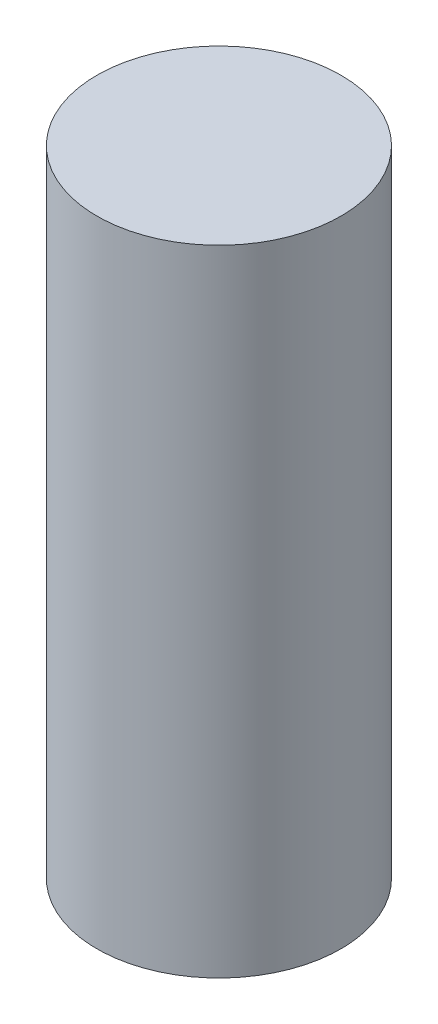
SolidWorks part; units mm, degrees
ref_plane "Front Plane" through (0, 0, 0) normal (0, 0, 1) x (1, 0, 0)
ref_plane "Top Plane" through (0, 0, 0) normal (0, 1, 0) x (1, 0, 0)
ref_plane "Right Plane" through (0, 0, 0) normal (1, 0, 0) x (0, 0, -1)
sketch "Sketch1" plane through (0, 0, 0) normal (0, 1, 0) x (1, 0, 0)
  circle A0 centre (0, 0) radius 2.5
  dimension "D1" = 5
extrude "Boss-Extrude1" add sketch "Sketch1" along normal blind 13
